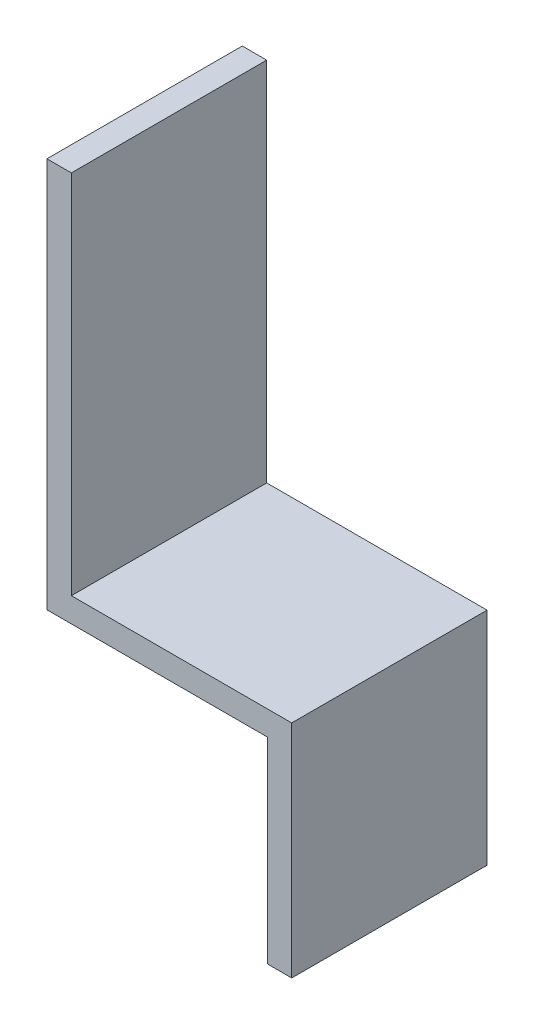
SolidWorks part; units mm, degrees
material "ABS"
ref_plane "X-Y Datum" through (0, 0, 0) normal (0, 0, 1) x (1, 0, 0)
ref_plane "X-Z Datum" through (0, 0, 0) normal (0, 1, 0) x (1, 0, 0)
ref_plane "Y-Z Datum" through (0, 0, 0) normal (1, 0, 0) x (0, 0, -1)
sketch "Sketch1" plane through (0, 0, 0) normal (0, 0, 1) x (1, 0, 0)
  line L0 (39.2838, -34.3838) -> (39.2838, -5.6599)
  line L1 (39.2838, -5.6599) -> (10.6322, -5.6599)
  line L2 (10.6322, -5.6599) -> (10.6322, 41.9526)
  line L3 (10.6322, 41.9526) -> (7.4572, 41.9526)
  line L4 (39.2838, -34.3838) -> (36.1088, -34.3838)
  line L5 (21.5026, -5.6599) -> (21.5026, -8.8349) construction
  line L6 (36.1088, -34.3838) -> (36.1088, -8.8349)
  line L7 (36.1088, -8.8349) -> (7.4572, -8.8349)
  line L8 (7.4572, -8.8349) -> (7.4572, 41.9526)
extrude "Boss-Extrude1" add sketch "Sketch1" along normal blind 25.4
